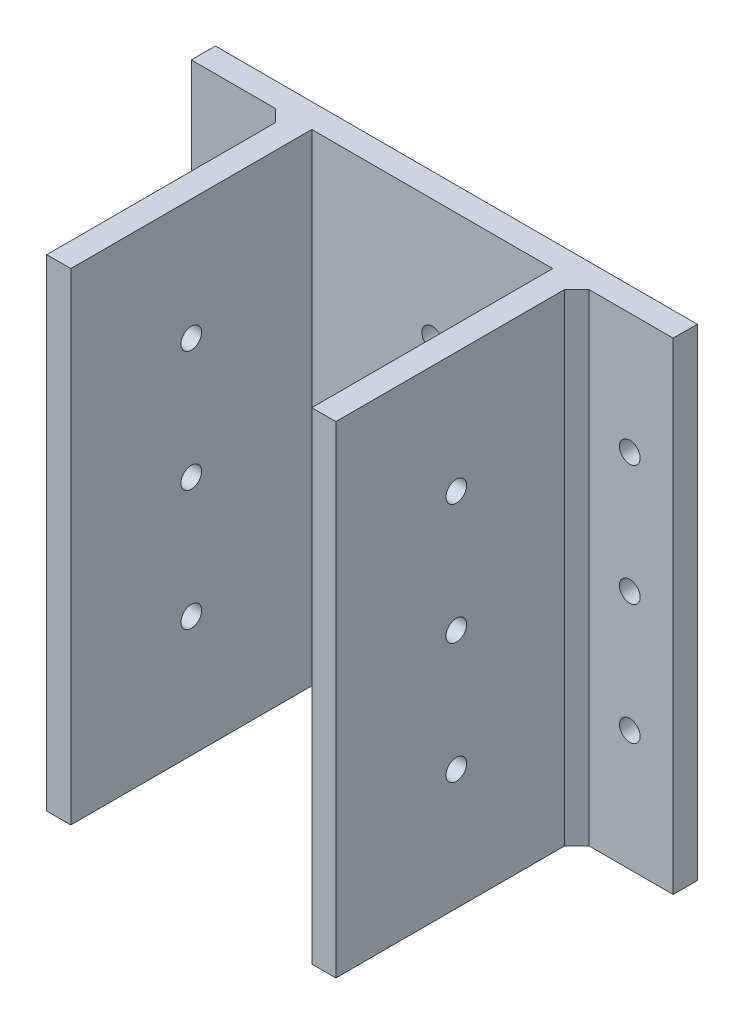
SolidWorks part; units mm, degrees
ref_plane "Front Plane" through (0, 0, 0) normal (0, 0, 1) x (1, 0, 0)
ref_plane "Top Plane" through (0, 0, 0) normal (0, 1, 0) x (1, 0, 0)
ref_plane "Right Plane" through (0, 0, 0) normal (1, 0, 0) x (0, 0, -1)
ref_plane "Plane1" through (20.5, 0, 0) normal (1, 0, 0) x (0, 0, -1)
sketch "Sketch1" plane through (0, 0, 0) normal (0, 0, 1) x (1, 0, 0)
  line L0 (-598.7546, 0) -> (29338.976, 0) construction
  line L1 (0, -598.7546) -> (0, 29338.976) construction
  line L3 (-50, 50) -> (50, 50)
  line L4 (-50, 50) -> (-50, -50)
  line L5 (-50, -50) -> (50, -50)
  line L6 (50, 50) -> (50, -50)
  dimension "D1" = 100
  dimension "D2" = 100
  dimension "D3" = 50
  dimension "D4" = 50
extrude "Boss-Extrude1" add sketch "Sketch1" along normal blind 5
sketch "Sketch2" plane through (0, 0, 5) normal (0, 0, 1) x (1, 0, 0)
  line L0 (-50, 0) -> (50, 0) construction
  line L1 (-50, 50) -> (-50, -50) construction
  line L2 (50, -50) -> (50, 50) construction
  line L3 (0, 50) -> (0, -50) construction
  line L4 (50, 50) -> (-50, 50) construction
  line L5 (-50, -50) -> (50, -50) construction
  line L7 (25, 50) -> (30, 50)
  line L8 (25, 50) -> (25, -50)
  line L9 (25, -50) -> (30, -50)
  line L10 (30, 50) -> (30, -50)
  dimension "D1" = 5
  dimension "D2" = 25
extrude "Boss-Extrude2" add sketch "Sketch2" along normal blind 50 contours L8 L7 L10 L9
sketch "Sketch3" plane through (0, 0, 0) normal (0, 0, -1) x (-1, 0, 0)
  line L0 (0, 55) -> (0, -55) construction
  line L1 (25, 50) -> (30, 50) construction
  line L2 (30, -50) -> (25, -50) construction
  line L3 (30, 50) -> (30, -50) construction
  line L4 (-25, 50) -> (-30, 50)
  line L5 (-30, 50) -> (-30, -50)
  line L6 (-30, -50) -> (-25, -50)
  line L7 (-25, -50) -> (-25, 50)
  line L8 (-25, 50) -> (-30, 50) construction
  line L9 (-30, 50) -> (-30, -50) construction
  line L10 (-30, -50) -> (-25, -50) construction
  line L11 (-25, -50) -> (-25, 50) construction
  line L12 (25, -50) -> (25, 50) construction
  line L13 (-50, 50) -> (50, 50) construction
  line L14 (50, -50) -> (-50, -50) construction
  circle A0 centre (0, 25) radius 2.15
  point P10 (0, 25)
  point P11 (0, 0)
  point P12 (0, -25)
  dimension "D2" = 25
  dimension "D3" = 25
  dimension "D4" = 50
  dimension "D1" = 0
extrude "Cut-Extrude1" cut sketch "Sketch3" against normal blind 10
mirror "Mirror1" about plane through (0, 0, 0) normal (1, 0, 0) of "Boss-Extrude2"
pattern_linear "LPattern1" count 3 spacing 25 along (0, -1, 0) of "Cut-Extrude1"
mirror "Mirror2" about plane through (20.5, 0, 0) normal (1, 0, 0) of "LPattern1", "Cut-Extrude1"
mirror "Mirror3" about plane through (0, 0, 0) normal (1, 0, 0) of "Mirror2"
chamfer "Chamfer1" distance 2.5 angle 45 2 edges at (30, 0, 5) (-30, 0, 5)
sketch "Sketch7" plane through (-30, 0, 0) normal (-1, 0, 0) x (0, 0, 1)
  line L4 (55, 50) -> (7.5, 50) construction
  line L5 (34.15, -400.4928) -> (34.15, 99.5072) construction
  line L6 (25.85, -400.4928) -> (25.85, 99.5072) construction
  line L7 (34.15, -400.4928) -> (34.15, 99.5072) construction
  line L8 (25.85, -400.4928) -> (25.85, 99.5072) construction
  circle A0 centre (30, 25) radius 2.15
  point P0 (30, -382.9928)
  point P6 (30, 25)
  dimension "D2" = 4.15
  dimension "D1" = 25
extrude "Cut-Extrude2" cut sketch "Sketch7" along direction (1, 0, 0) on the side against the normal blind 60 contours A0
sketch "Sketch8" plane through (-30, 0, 0) normal (-1, 0, 0) x (0, 0, 1)
  line L1 (30, 25) -> (30, -25) construction
  circle A0 centre (30, 0) radius 2.15
  circle A1 centre (30, 25) radius 2.15 construction
  circle A2 centre (30, 25) radius 2.15
  dimension "D2" = 25
extrude "Cut-Extrude3" cut sketch "Sketch8" against normal blind 60
mirror "Mirror4" about plane through (0, 0, 0) normal (0, 1, 0) of "Cut-Extrude2"
